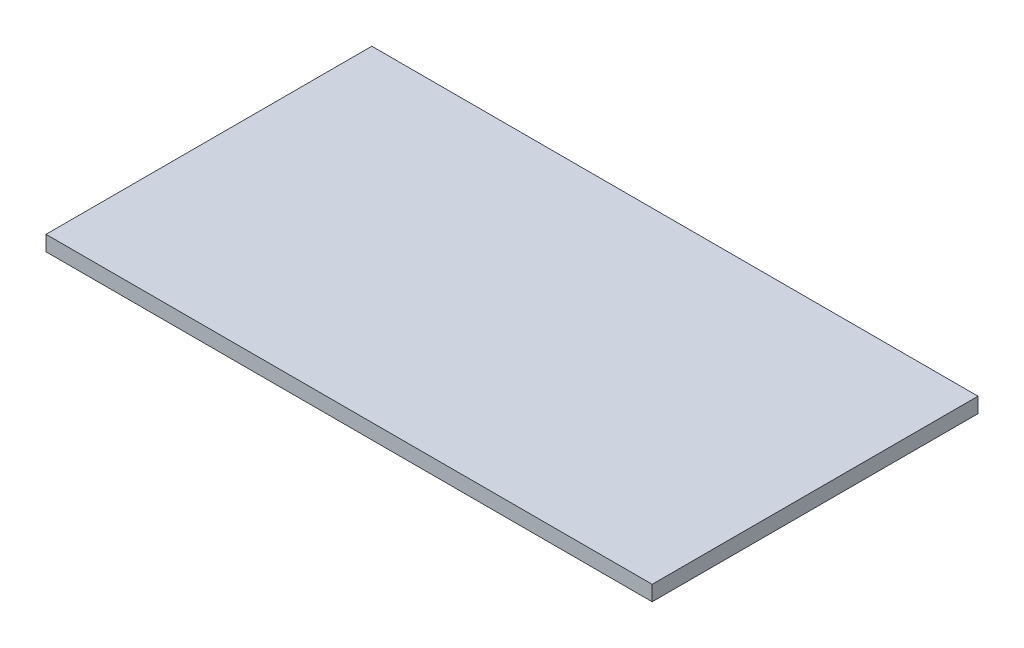
SolidWorks part; units mm, degrees
material "Acrylic (Medium-high impact)"
ref_plane "Front Plane" through (0, 0, 0) normal (0, 0, 1) x (1, 0, 0)
ref_plane "Top Plane" through (0, 0, 0) normal (0, 1, 0) x (1, 0, 0)
ref_plane "Right Plane" through (0, 0, 0) normal (1, 0, 0) x (0, 0, -1)
sketch "Sketch1" plane through (0, 0, 0) normal (0, 1, 0) x (1, 0, 0)
  line L1 (-40, 21.5) -> (40, 21.5)
  line L2 (-40, 21.5) -> (-40, -21.5)
  line L3 (-40, -21.5) -> (40, -21.5)
  line L4 (40, 21.5) -> (40, -21.5)
  line L5 (-40, 21.5) -> (40, -21.5) construction
  line L6 (-40, -21.5) -> (40, 21.5) construction
  point P0 (0, 0)
  point P5 (0, 0)
  dimension "D1" = 80
  dimension "D2" = 43
extrude "Boss-Extrude1" add sketch "Sketch1" along normal blind 2
